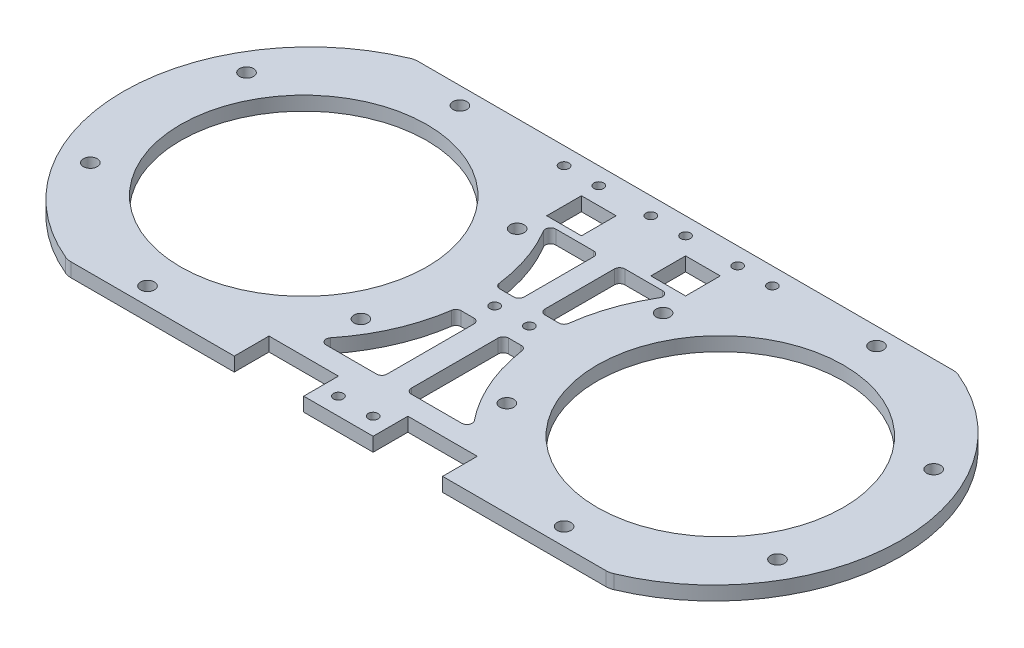
SolidWorks part; units mm, degrees
ref_plane "前视基准面" through (0, 0, 0) normal (0, 0, 1) x (1, 0, 0)
ref_plane "上视基准面" through (0, 0, 0) normal (0, 1, 0) x (1, 0, 0)
ref_plane "右视基准面" through (0, 0, 0) normal (1, 0, 0) x (0, 0, -1)
sketch "草图1" plane through (0, 0, 0) normal (0, 1, 0) x (1, 0, 0)
  line L0 (0, -36.6698) -> (0, 70.1328) construction
  line L1 (32.6264, 0) -> (115.7429, 0) construction
  line L2 (-77.0235, 50) -> (77.0235, 50)
  line L3 (60, -45) -> (98.9711, -22.5) construction
  line L4 (98.9711, -22.5) -> (98.9711, 22.5) construction
  line L5 (98.9711, 22.5) -> (60, 45) construction
  line L6 (60, 45) -> (21.0289, 22.5) construction
  line L7 (21.0289, 22.5) -> (21.0289, -22.5) construction
  line L8 (21.0289, -22.5) -> (60, -45) construction
  line L9 (-77.0235, -50) -> (77.0235, -50) construction
  line L10 (-77.0235, -50) -> (-30, -50)
  line L11 (-5, 45) -> (5, 45) construction
  line L12 (-5, 45) -> (-5, -45) construction
  line L13 (-5, -45) -> (5, -45) construction
  line L14 (5, 45) -> (5, -45) construction
  line L15 (-5, 45) -> (5, -45) construction
  line L16 (-5, -45) -> (5, 45) construction
  line L17 (10, -50) -> (-10, -50) construction
  line L18 (10, -50) -> (10, 50) construction
  line L19 (10, 50) -> (-10, 50) construction
  line L20 (-10, -50) -> (-10, 50) construction
  line L21 (10, -50) -> (-10, 50) construction
  line L22 (10, 50) -> (-10, -50) construction
  line L23 (-20, 40) -> (-10, 40)
  line L24 (-20, 40) -> (-20, 30)
  line L25 (-20, 30) -> (-10, 30)
  line L26 (-10, 40) -> (-10, 30)
  line L27 (-20, 40) -> (-10, 30) construction
  line L28 (-20, 30) -> (-10, 40) construction
  line L29 (-30, -50) -> (-10, -50) construction
  line L30 (-30, -50) -> (-30, -40)
  line L31 (-30, -40) -> (-10, -40)
  line L32 (-10, -50) -> (-10, -40)
  line L33 (-30, -50) -> (-10, -40) construction
  line L34 (-30, -40) -> (-10, -50) construction
  line L35 (10, -50) -> (10, -40)
  line L36 (30, -40) -> (10, -40)
  line L37 (30, -50) -> (30, -40)
  line L38 (-10, -50) -> (10, -50)
  line L39 (30, -50) -> (77.0235, -50)
  line L40 (20, 30) -> (10, 30)
  line L41 (10, 40) -> (10, 30)
  line L42 (20, 40) -> (10, 40)
  line L43 (20, 40) -> (20, 30)
  line L44 (-15.3753, 28) -> (-4.5, 28)
  line L45 (-3, 26.5) -> (-3, 6.5)
  line L46 (-4.5, 5) -> (-8.5086, 5)
  line L47 (15.3753, 28) -> (4.5, 28)
  line L48 (3, 26.5) -> (3, 6.5)
  line L49 (4.5, 5) -> (8.5086, 5)
  line L50 (-3.5, -7.5) -> (-3.5, -32.5)
  line L51 (-5, -34) -> (-19.5357, -34)
  line L52 (-5, -6) -> (-8.6448, -6)
  line L53 (5, -6) -> (8.6448, -6)
  line L54 (3.5, -7.5) -> (3.5, -32.5)
  line L55 (5, -34) -> (19.5357, -34)
  circle A0 centre (60, 0) radius 35.5
  circle A1 centre (60, 0) radius 45 construction
  circle A2 centre (60, 0) radius 38.9711 construction
  circle A3 centre (60, 45) radius 2
  circle A4 centre (21.0289, 22.5) radius 2
  circle A5 centre (21.0289, -22.5) radius 2
  circle A6 centre (60, -45) radius 2
  circle A7 centre (98.9711, -22.5) radius 2
  circle A8 centre (98.9711, 22.5) radius 2
  circle A9 centre (-60, 0) radius 45 construction
  circle A10 centre (-60, 0) radius 35.5
  circle A11 centre (-98.9711, -22.5) radius 2
  circle A12 centre (-98.9711, 22.5) radius 2
  circle A13 centre (-60, 45) radius 2
  circle A14 centre (-21.0289, 22.5) radius 2
  circle A15 centre (-21.0289, -22.5) radius 2
  circle A16 centre (-60, -45) radius 2
  arc A17 (78.9499, 49.614) -> (78.9499, -49.614) centre (58.2353, 0) cw
  arc A18 (77.0235, 50) -> (78.9499, 49.614) centre (77.0235, 45) cw
  arc A19 (77.0235, -50) -> (78.9499, -49.614) centre (77.0235, -45) ccw
  arc A20 (-77.0235, -50) -> (-78.9499, -49.614) centre (-77.0235, -45) cw
  arc A21 (-78.9499, 49.614) -> (-78.9499, -49.614) centre (-58.2353, 0) ccw
  arc A22 (-77.0235, 50) -> (-78.9499, 49.614) centre (-77.0235, 45) ccw
  circle A23 centre (-5, 45) radius 1.4
  circle A24 centre (5, 45) radius 1.4
  circle A25 centre (5, -45) radius 1.4
  circle A26 centre (-5, -45) radius 1.4
  circle A27 centre (-5, 0) radius 1.4
  circle A28 centre (5, 0) radius 1.4
  circle A29 centre (-60, 0) radius 48.9 construction
  arc A31 (-16.6651, 25.7341) -> (-9.9968, 6.3121) centre (-60, 0) cw
  arc A32 (-4.5, 28) -> (-3, 26.5) centre (-4.5, 26.5) cw
  arc A33 (-3, 6.5) -> (-4.5, 5) centre (-4.5, 6.5) cw
  arc A34 (-8.5086, 5) -> (-9.9968, 6.3121) centre (-8.5086, 6.5) cw
  arc A35 (-15.3753, 28) -> (-16.6651, 25.7341) centre (-15.3753, 26.5) ccw
  arc A36 (4.5, 28) -> (3, 26.5) centre (4.5, 26.5) ccw
  arc A37 (3, 6.5) -> (4.5, 5) centre (4.5, 6.5) ccw
  arc A38 (8.5086, 5) -> (9.9968, 6.3121) centre (8.5086, 6.5) ccw
  arc A39 (15.3753, 28) -> (16.6651, 25.7341) centre (15.3753, 26.5) cw
  arc A40 (16.6651, 25.7341) -> (9.9968, 6.3121) centre (60, 0) ccw
  arc A41 (-10.129, -7.2832) -> (-20.7052, -31.5607) centre (-60, 0) cw
  arc A42 (-8.6448, -6) -> (-10.129, -7.2832) centre (-8.6448, -7.5) ccw
  arc A43 (-3.5, -7.5) -> (-5, -6) centre (-5, -7.5) ccw
  arc A44 (-3.5, -32.5) -> (-5, -34) centre (-5, -32.5) cw
  arc A45 (-19.5357, -34) -> (-20.7052, -31.5607) centre (-19.5357, -32.5) cw
  arc A46 (3.5, -7.5) -> (5, -6) centre (5, -7.5) cw
  arc A47 (3.5, -32.5) -> (5, -34) centre (5, -32.5) ccw
  arc A48 (8.6448, -6) -> (10.129, -7.2832) centre (8.6448, -7.5) cw
  arc A49 (19.5357, -34) -> (20.7052, -31.5607) centre (19.5357, -32.5) ccw
  arc A50 (10.129, -7.2832) -> (20.7052, -31.5607) centre (60, 0) ccw
  circle A51 centre (20, 45) radius 1.4
  circle A52 centre (30, 45) radius 1.4
  circle A53 centre (-30, 45) radius 1.4
  circle A54 centre (-20, 45) radius 1.4
  circle A55 centre (60, 0) radius 48.9 construction
  point P38 (0, 0)
  point P42 (105, 0)
  point P43 (78, 50)
  point P47 (112, 0)
  point P49 (0, -50)
  point P55 (0, 50)
  point P68 (0, 0)
  point P73 (-15, 35)
  point P78 (-20, -45)
  point P144 (0, 0)
  point P145 (0, 0)
  point P146 (0, 0)
  dimension "D1" = 71
  dimension "D3" = 90
  dimension "D4" = 4
  dimension "D8" = 5
  dimension "D9" = 10
  dimension "D11" = 2.8
  dimension "D17" = 97.8
  dimension "D20" = 1.5
  dimension "D22" = 1.5
  dimension "D24" = 1.5
  dimension "D27" = 1.5
  dimension "D2" = 60
  dimension "D5" = 50
  dimension "D6" = 18
  dimension "D7" = 7
  dimension "D10" = 5
  dimension "D12" = 20
  dimension "D13" = 10
  dimension "D14" = 10
  dimension "D15" = 10
  dimension "D16" = 20
  dimension "D18" = 2
  dimension "D19" = 3
  dimension "D21" = 5
  dimension "D23" = 3.5
  dimension "D25" = 6
  dimension "D26" = 6
  dimension "D28" = 10
extrude "凸台-拉伸1" add sketch "草图1" along normal blind 4 contours L2 A22 A21 A20 L10 L30 L31 L32 L38 L35 L36 L37 L39 A19 A17 A18 A28 A27 A26 A25 A24 A23 A16 A14 A12 A10 A8 A7 A6 A5 A4 A3 A0
